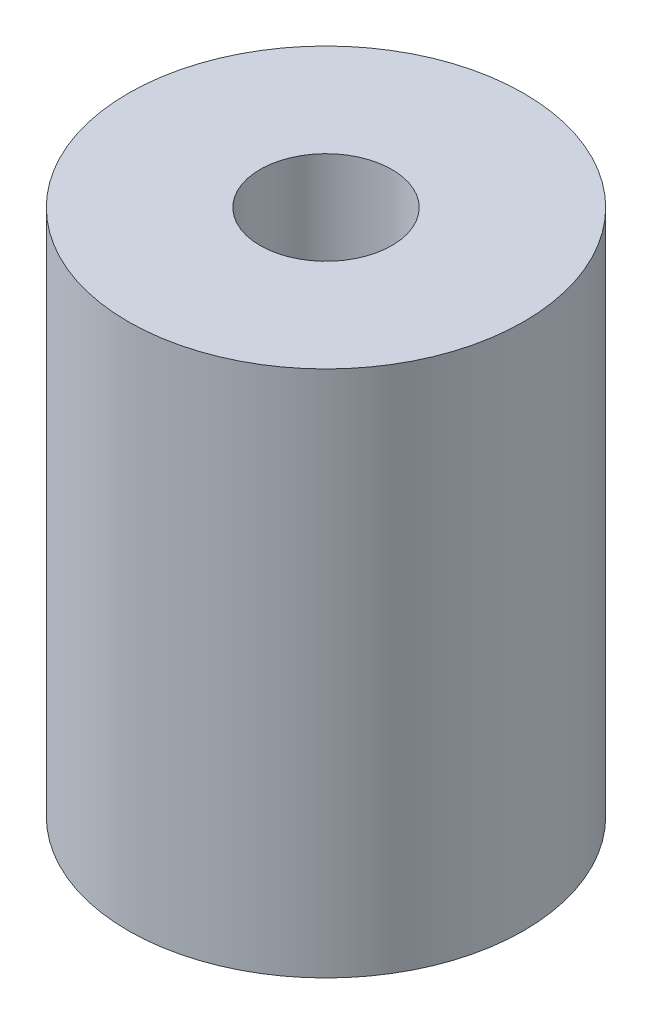
SolidWorks part; units mm, degrees
ref_plane "Front Plane" through (0, 0, 0) normal (0, 0, 1) x (1, 0, 0)
ref_plane "Top Plane" through (0, 0, 0) normal (0, 1, 0) x (1, 0, 0)
ref_plane "Right Plane" through (0, 0, 0) normal (1, 0, 0) x (0, 0, -1)
sketch "Sketch1" plane through (0, 0, 0) normal (0, 1, 0) x (1, 0, 0)
  circle A0 centre (0, 0) radius 1.5875
  circle A1 centre (0, 0) radius 9.525
  dimension "D1" = 3.175
  dimension "D2" = 19.05
extrude "Boss-Extrude1" add sketch "Sketch1" along normal mid plane 25.4
sketch "Sketch2" plane through (0, 12.7, 0) normal (0, 1, 0) x (1, 0, 0)
  circle A0 centre (0, 0) radius 3.175
  dimension "D1" = 6.35
extrude "Cut-Extrude1" cut sketch "Sketch2" against normal blind 8.4667
mirror "Mirror1" about plane through (0, 0, 0) normal (0, 1, 0) of "Cut-Extrude1"
